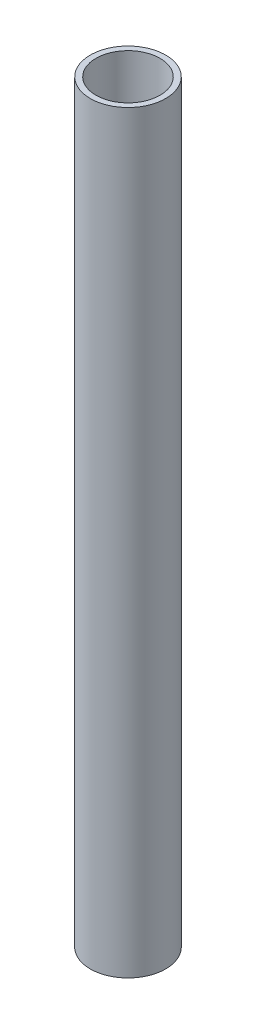
SolidWorks part; units mm, degrees
ref_plane "前视基准面" through (0, 0, 0) normal (0, 0, 1) x (1, 0, 0)
ref_plane "上视基准面" through (0, 0, 0) normal (0, 1, 0) x (1, 0, 0)
ref_plane "右视基准面" through (0, 0, 0) normal (1, 0, 0) x (0, 0, -1)
other "Configuration Table"
sketch "草图1" plane through (0, 0, 0) normal (0, 1, 0) x (1, 0, 0)
  circle A14 centre (0, 0) radius 16
  circle A15 centre (0, 0) radius 13.6
  dimension "D1" = 32
  dimension "D2" = 2.4
extrude "凸台-拉伸1" add sketch "草图1" along normal blind 320
